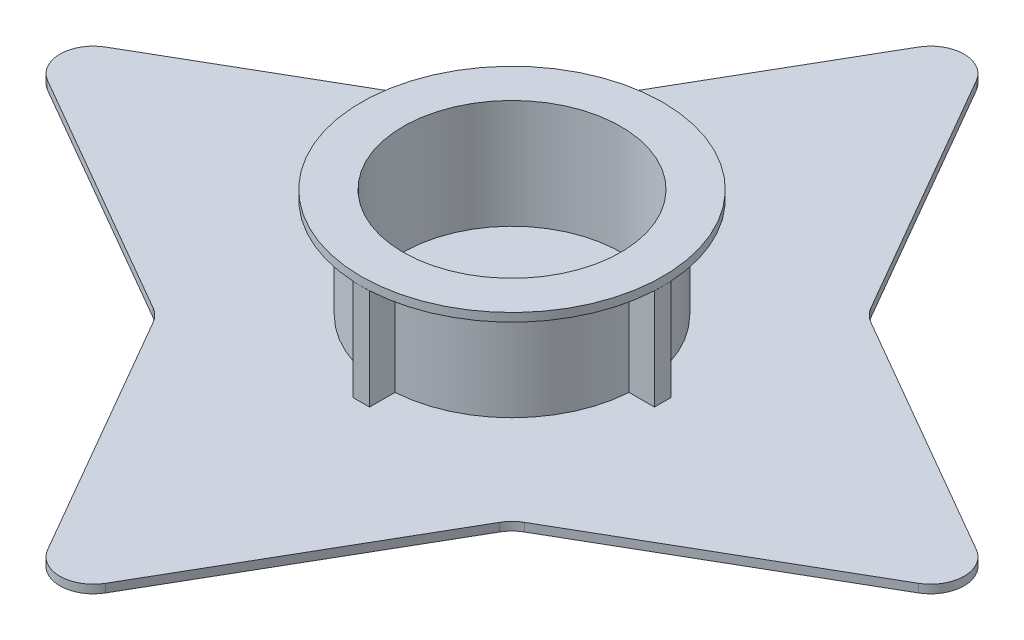
SolidWorks part; units mm, degrees
ref_plane "Alzado" through (0, 0, 0) normal (0, 0, 1) x (1, 0, 0)
ref_plane "Planta" through (0, 0, 0) normal (0, 1, 0) x (1, 0, 0)
ref_plane "Vista lateral" through (0, 0, 0) normal (1, 0, 0) x (0, 0, -1)
sketch "Croquis1" plane through (0, 0, 0) normal (0, 1, 0) x (1, 0, 0)
  line L0 (0, 0) -> (0, 400) construction
  line L1 (0, 0) -> (282.8427, 282.8427) construction
  line L2 (106.066, 106.066) -> (289.7777, 0)
  line L3 (106.066, -106.066) -> (289.7777, 0)
  line L4 (0, 0) -> (400, 0) construction
  line L5 (106.066, 106.066) -> (0, 289.7777)
  line L6 (106.066, -106.066) -> (0, -289.7777)
  line L7 (-106.066, -106.066) -> (0, -289.7777)
  line L8 (-106.066, -106.066) -> (-289.7777, 0)
  line L9 (-106.066, 106.066) -> (-289.7777, 0)
  line L10 (-106.066, 106.066) -> (0, 289.7777)
  line L11 (106.066, 106.066) -> (365.7249, 106.066) construction
  dimension "D1" = 45
  dimension "D2" = 30
  dimension "D3" = 150
extrude "Extruir1" add sketch "Croquis1" along normal blind 5
fillet "Redondeo1" radius 20 8 edges at (106.066, 2.5, -106.066) (0, 2.5, -289.7777) (-106.066, 2.5, -106.066) (-289.7777, 2.5, 0) (289.7777, 2.5, 0) (106.066, 2.5, 106.066) (0, 2.5, 289.7777) (-106.066, 2.5, 106.066)
sketch "Croquis2" plane through (0, 5, 0) normal (0, 1, 0) x (1, 0, 0)
  line L0 (0, 0) -> (179.3407, 0) construction
  line L1 (74.8331, 5) -> (90, 5)
  line L2 (74.8331, -5) -> (90, -5)
  line L3 (90, 5) -> (90, -5)
  line L4 (5, -74.8331) -> (5, -90)
  line L5 (-5, -74.8331) -> (-5, -90)
  line L6 (5, -90) -> (-5, -90)
  line L7 (-74.8331, -5) -> (-90, -5)
  line L8 (-74.8331, 5) -> (-90, 5)
  line L9 (-90, -5) -> (-90, 5)
  line L10 (-5, 74.8331) -> (-5, 90)
  line L11 (5, 74.8331) -> (5, 90)
  line L12 (-5, 90) -> (5, 90)
  arc A0 (-74.8331, -5) -> (-5, -74.8331) centre (0, 0) ccw
  arc A1 (5, -74.8331) -> (74.8331, -5) centre (0, 0) ccw
  arc A2 (-5, 74.8331) -> (-74.8331, 5) centre (0, 0) ccw
  arc A3 (74.8331, 5) -> (5, 74.8331) centre (0, 0) ccw
  dimension "D1" = 150
  dimension "D2" = 90
  dimension "D3" = 10
extrude "Extruir3" add sketch "Croquis2" along normal blind 60
sketch "Croquis4" plane through (0, 65, 0) normal (0, 1, 0) x (1, 0, 0)
  circle A0 centre (0, 0) radius 90
  dimension "D1" = 180
extrude "Extruir4" add sketch "Croquis4" along normal blind 5
sketch "Croquis5" plane through (0, 70, 0) normal (0, 1, 0) x (1, 0, 0)
  circle A0 centre (0, 0) radius 65
  dimension "D1" = 130
extrude "Extruir5" cut sketch "Croquis5" against normal up to surface (65 mm away) up to face at (0, 5, 0)
